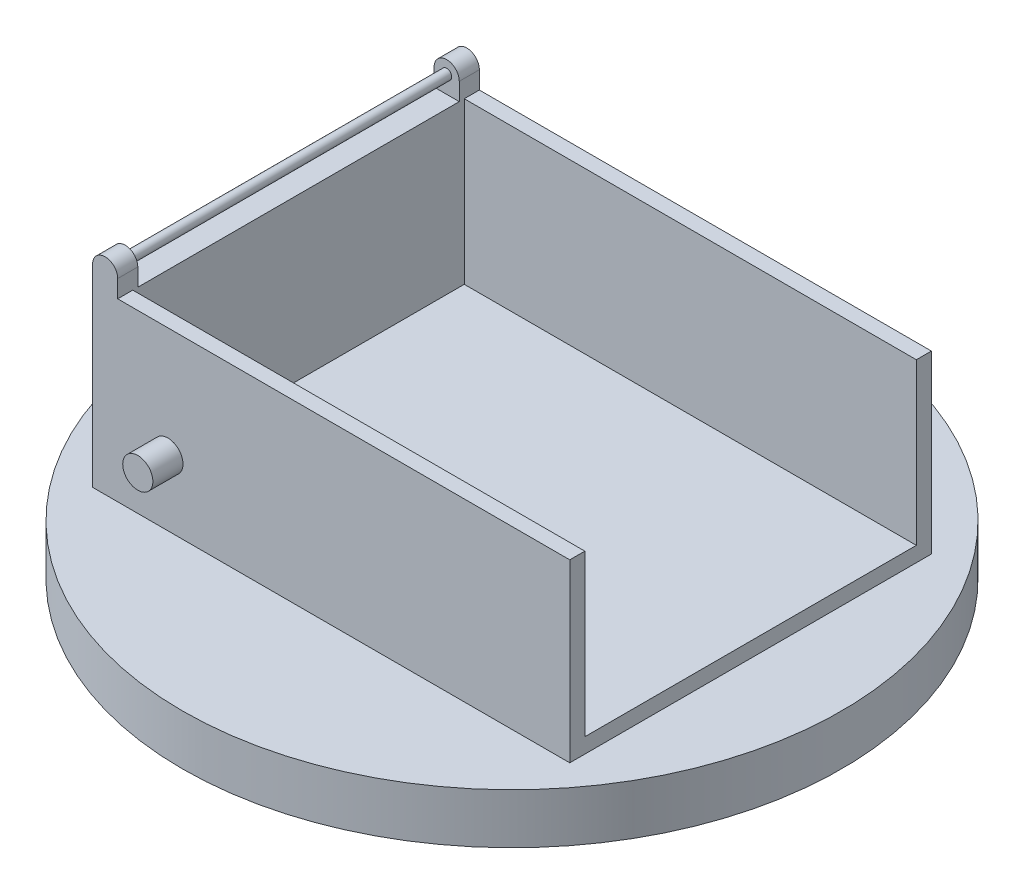
SolidWorks part; units mm, degrees
ref_plane "Front Plane" through (0, 0, 0) normal (0, 0, 1) x (1, 0, 0)
ref_plane "Top Plane" through (0, 0, 0) normal (0, 1, 0) x (1, 0, 0)
ref_plane "Right Plane" through (0, 0, 0) normal (1, 0, 0) x (0, 0, -1)
sketch "Sketch1" plane through (0, 0, 0) normal (0, 1, 0) x (1, 0, 0)
  line L1 (-47.5, -36) -> (47.5, -36)
  line L2 (-47.5, -36) -> (-47.5, 36)
  line L3 (-47.5, 36) -> (47.5, 36)
  line L4 (47.5, -36) -> (47.5, 36)
  line L5 (-47.5, -36) -> (47.5, 36) construction
  line L6 (-47.5, 36) -> (47.5, -36) construction
  point P0 (0, 0)
  dimension "D1" = 72
  dimension "D2" = 95
extrude "Boss-Extrude1" add sketch "Sketch1" along normal blind 35
sketch "Sketch5" plane through (0, 35, 0) normal (0, 1, 0) x (1, 0, 0)
  line L0 (47.5, -36) -> (47.5, 36) construction
  line L1 (-42.5, -33) -> (47.5, -33)
  line L2 (-42.5, -33) -> (-42.5, 33)
  line L3 (-42.5, 33) -> (47.5, 33)
  line L4 (47.5, -33) -> (47.5, 33)
  line L5 (-47.5, -36) -> (47.5, -36) construction
  line L7 (-47.5, 36) -> (-47.5, -36) construction
  dimension "D1" = 66
  dimension "D2" = 3
  dimension "D3" = 5
extrude "Cut-Extrude1" cut sketch "Sketch5" against normal blind 32
sketch "Sketch9" plane through (0, 0, 36) normal (0, 0, 1) x (1, 0, 0)
  line L0 (-47.5, 35) -> (47.5, 35) construction
  line L1 (-47.5, 35) -> (-47.5, 0) construction
  circle A0 centre (-32.5, 13) radius 3
  dimension "D1" = 6
  dimension "D2" = 22
  dimension "D3" = 15
extrude "Boss-Extrude4" add sketch "Sketch9" along normal blind 6
mirror "Mirror3" about plane through (0, 0, 0) normal (0, 0, 1) of "Boss-Extrude4"
sketch "Sketch10" plane through (0, 0, 36) normal (0, 0, 1) x (1, 0, 0)
  line L0 (-42.5, 35) -> (-42.5, 38.5)
  line L1 (-47.5, 35) -> (47.5, 35) construction
  line L2 (-47.5, 35) -> (-47.5, 38.5)
  line L4 (-47.5, 35) -> (-42.5, 35)
  arc A0 (-42.5, 38.5) -> (-47.5, 38.5) centre (-45, 38.5) ccw
  dimension "D4" = 2.5
  dimension "D1" = 5
  dimension "D3" = 3.5
  dimension "D5" = 3.5
extrude "Boss-Extrude5" add sketch "Sketch10" against normal blind 4
mirror "Mirror4" about plane through (0, 0, 0) normal (0, 0, 1) of "Boss-Extrude5"
sketch "Sketch11" plane through (0, 0, 0) normal (0, -1, 0) x (1, 0, 0)
  circle A0 centre (0, 0) radius 65.6118
extrude "Boss-Extrude6" add sketch "Sketch11" along normal blind 10 contours A0
sketch "Sketch12" plane through (0, -10, 0) normal (0, -1, 0) x (1, 0, 0)
  circle A0 centre (0, 0) radius 17.6404
  circle A1 centre (0, 0) radius 8.1224
extrude "Boss-Extrude7" add sketch "Sketch12" along normal blind 30
sketch "Sketch13" plane through (0, 0, 36) normal (0, 0, 1) x (1, 0, 0)
  circle A0 centre (-45, 38.5) radius 1
  dimension "D1" = 2
extrude "Boss-Extrude8" add sketch "Sketch13" against normal up to surface (68 mm away) contours A0 up to face at (-45, 37.375, -32)
